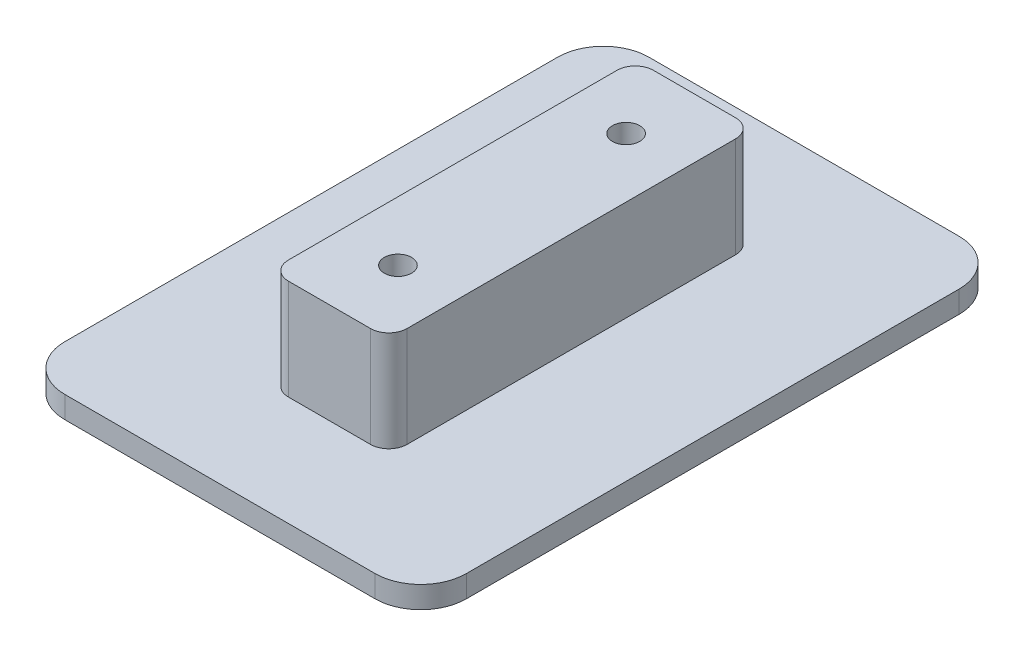
SolidWorks part; units mm, degrees
ref_plane "Front Plane" through (0, 0, 0) normal (0, 0, 1) x (1, 0, 0)
ref_plane "Top Plane" through (0, 0, 0) normal (0, 1, 0) x (1, 0, 0)
ref_plane "Right Plane" through (0, 0, 0) normal (1, 0, 0) x (0, 0, -1)
sketch "Sketch1" plane through (0, 0, 0) normal (0, 1, 0) x (1, 0, 0)
  line L1 (-85, 160) -> (85, 160)
  line L2 (-110, 135) -> (-110, -135)
  line L3 (-85, -160) -> (85, -160)
  line L4 (110, 135) -> (110, -135)
  line L5 (-110, 160) -> (110, -160) construction
  line L6 (-110, -160) -> (110, 160) construction
  arc A0 (85, 160) -> (110, 135) centre (85, 135) cw
  arc A1 (-110, 135) -> (-85, 160) centre (-85, 135) cw
  arc A2 (110, -135) -> (85, -160) centre (85, -135) cw
  arc A3 (-85, -160) -> (-110, -135) centre (-85, -135) cw
  point P0 (0, 0)
  dimension "D3" = 25
  dimension "D4" = 25
  dimension "D1" = 220
  dimension "D2" = 320
extrude "Boss-Extrude1" add sketch "Sketch1" along normal blind 12
sketch "Sketch2" plane through (0, 12, 0) normal (0, 1, 0) x (1, 0, 0)
  line L0 (0, -62.5) -> (0, 62.5) construction
  line L1 (-22.5, 100) -> (22.5, 100)
  line L2 (-32.5, 90) -> (-32.5, -90)
  line L3 (-22.5, -100) -> (22.5, -100)
  line L4 (32.5, 90) -> (32.5, -90)
  line L5 (-32.5, 100) -> (32.5, -100) construction
  line L6 (-32.5, -100) -> (32.5, 100) construction
  arc A0 (-22.5, -100) -> (-32.5, -90) centre (-22.5, -90) cw
  arc A1 (32.5, -90) -> (22.5, -100) centre (22.5, -90) cw
  arc A2 (22.5, 100) -> (32.5, 90) centre (22.5, 90) cw
  arc A3 (-22.5, 100) -> (-32.5, 90) centre (-22.5, 90) ccw
  circle A6 centre (0, 62.5) radius 7.5
  circle A7 centre (0, -62.5) radius 7.5
  point P0 (0, 0)
  point P21 (0, 0)
  dimension "D3" = 10
  dimension "D5" = 15
  dimension "D6" = 15
  dimension "D1" = 200
  dimension "D2" = 65
  dimension "D4" = 125
extrude "Boss-Extrude2" add sketch "Sketch2" along normal blind 55
